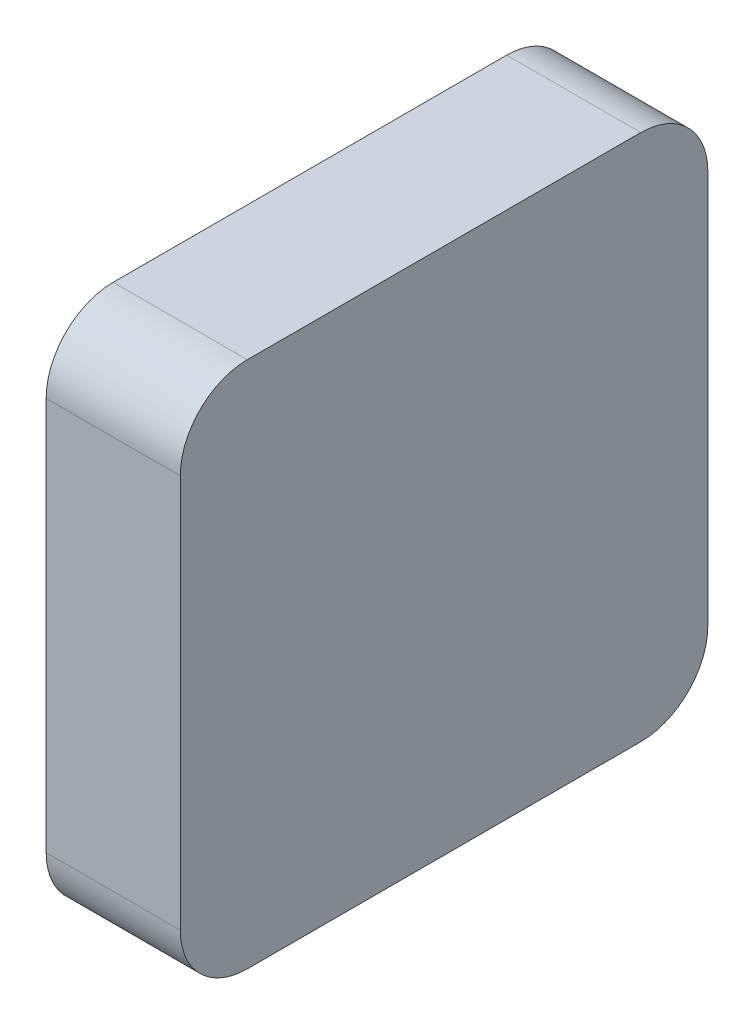
SolidWorks part; units mm, degrees
material "PPE"
ref_plane "Front Plane" through (0, 0, 0) normal (1, 0, 0) x (0, 1, 0)
ref_plane "Top Plane" through (0, 0, 0) normal (0, 0, 1) x (0, 1, 0)
ref_plane "Right Plane" through (0, 0, 0) normal (0, 1, 0) x (-1, 0, 0)
sketch "Sketch1" plane through (0, 0, 0) normal (1, 0, 0) x (0, 1, 0)
  line L1 (-11.176, -14.986) -> (11.176, -14.986)
  line L2 (-14.986, -11.176) -> (-14.986, 11.176)
  line L3 (-11.176, 14.986) -> (11.176, 14.986)
  line L4 (14.986, -11.176) -> (14.986, 11.176)
  line L5 (-14.986, -14.986) -> (14.986, 14.986) construction
  line L6 (-14.986, 14.986) -> (14.986, -14.986) construction
  arc A0 (-11.176, -14.986) -> (-14.986, -11.176) centre (-11.176, -11.176) cw
  arc A1 (11.176, -14.986) -> (14.986, -11.176) centre (11.176, -11.176) ccw
  arc A2 (11.176, 14.986) -> (14.986, 11.176) centre (11.176, 11.176) cw
  arc A3 (-14.986, 11.176) -> (-11.176, 14.986) centre (-11.176, 11.176) cw
  point P0 (0, 0)
  dimension "D2" = 3.81
  dimension "D1" = 29.972
extrude "Boss-Extrude1" add sketch "Sketch1" along normal blind 7.62
